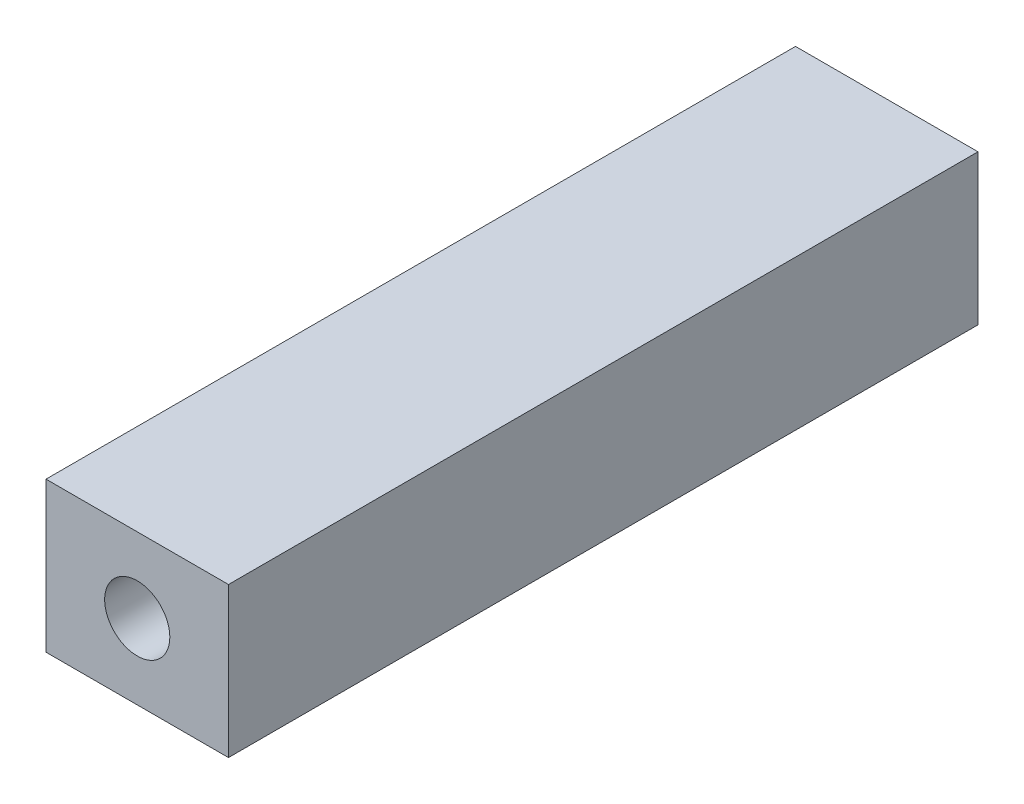
SolidWorks part; units mm, degrees
ref_plane "Front Plane" through (0, 0, 0) normal (0, 0, 1) x (1, 0, 0)
ref_plane "Top Plane" through (0, 0, 0) normal (0, 1, 0) x (1, 0, 0)
ref_plane "Right Plane" through (0, 0, 0) normal (1, 0, 0) x (0, 0, -1)
sketch "Sketch1" plane through (0, 0, 0) normal (0, 0, 1) x (1, 0, 0)
  line L1 (-14, 11.5) -> (14, 11.5)
  line L2 (-14, 11.5) -> (-14, -11.5)
  line L3 (-14, -11.5) -> (14, -11.5)
  line L4 (14, 11.5) -> (14, -11.5)
  line L5 (-14, 11.5) -> (14, -11.5) construction
  line L6 (-14, -11.5) -> (14, 11.5) construction
  circle A0 centre (0, 0) radius 5
  point P0 (0, 0)
  dimension "D3" = 10
  dimension "D1" = 28
  dimension "D2" = 23
extrude "Boss-Extrude1" add sketch "Sketch1" along normal mid plane 115
